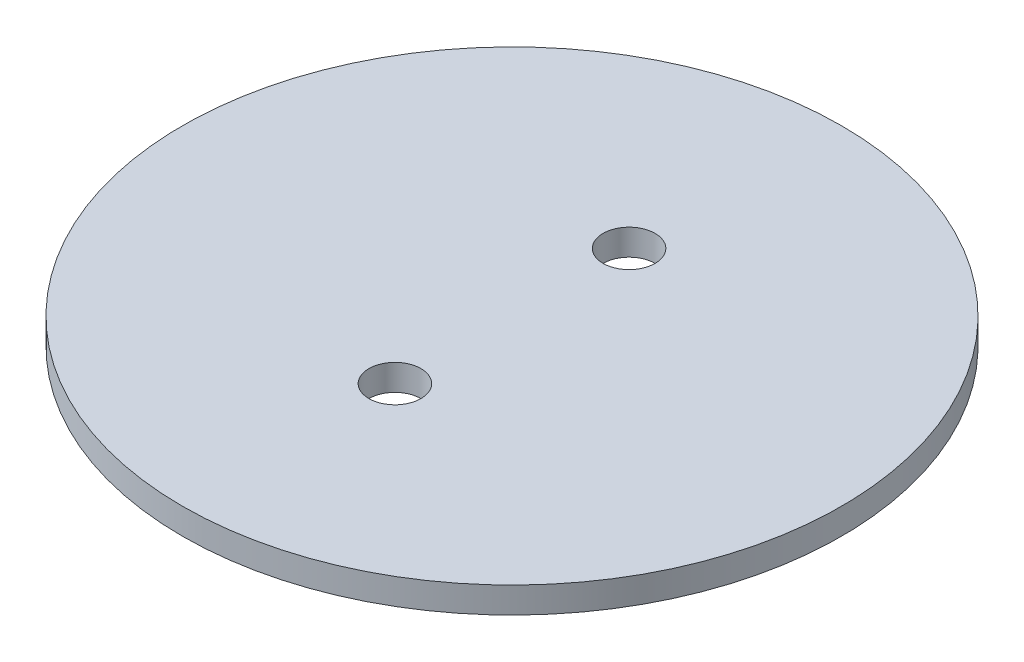
SolidWorks part; units mm, degrees
ref_plane "Front Plane" through (0, 0, 0) normal (0, 0, 1) x (1, 0, 0)
ref_plane "Top Plane" through (0, 0, 0) normal (0, 1, 0) x (1, 0, 0)
ref_plane "Right Plane" through (0, 0, 0) normal (1, 0, 0) x (0, 0, -1)
sketch "Sketch1" plane through (0, 0, 0) normal (0, 1, 0) x (1, 0, 0)
  line L0 (-28.5, 0) -> (28.5, 0) construction
  line L1 (0, 0) -> (0, 13.5)
  line L2 (0, 0) -> (0, -13.5)
  circle A0 centre (0, 0) radius 38
  circle A1 centre (28.5, 0) radius 3 construction
  circle A2 centre (-28.5, 0) radius 3 construction
  circle A3 centre (0, 13.5) radius 3
  circle A4 centre (0, -13.5) radius 3
  circle A5 centre (-28.5, 0) radius 6.25 construction
  circle A6 centre (0, 13.5) radius 12.5 construction
  circle A7 centre (0, -13.5) radius 12.5 construction
  circle A8 centre (28.5, 0) radius 6.25 construction
  point P11 (0, 0)
  dimension "D1" = 76
  dimension "D3" = 6
  dimension "D4" = 13.5
  dimension "D5" = 6
  dimension "D6" = 12.5
  dimension "D7" = 25
  dimension "D2" = 57
extrude "Boss-Extrude1" add sketch "Sketch1" against normal blind 3
